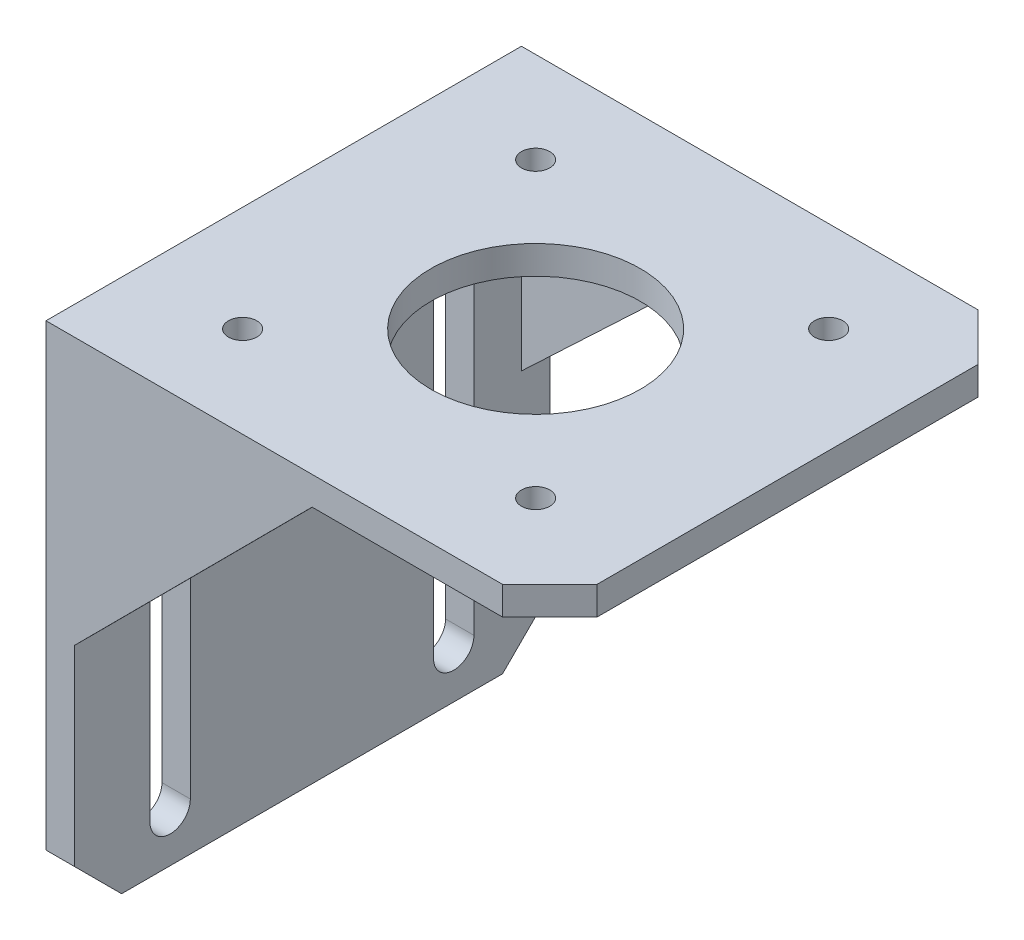
SolidWorks part; units mm, degrees
ref_plane "Front Plane" through (0, 0, 0) normal (0, 0, 1) x (1, 0, 0)
ref_plane "Top Plane" through (0, 0, 0) normal (0, 1, 0) x (1, 0, 0)
ref_plane "Right Plane" through (0, 0, 0) normal (1, 0, 0) x (0, 0, -1)
sketch "Sketch1" plane through (0, 0, 0) normal (1, 0, 0) x (0, 0, -1)
  line L1 (-14.9989, 23.6362) -> (35.3011, 23.6362)
  line L2 (-14.9989, 23.6362) -> (-14.9989, -29.8638)
  line L3 (-14.9989, -29.8638) -> (35.3011, -29.8638)
  line L4 (35.3011, 23.6362) -> (35.3011, -29.8638)
  line L5 (-6.9989, -24.8184) -> (-6.9989, 18.3152)
  line L6 (27.2711, 18.3152) -> (27.2711, -24.8184)
  line L7 (-2.7289, 18.3152) -> (-2.7289, -24.8184)
  line L10 (23.0011, 18.3152) -> (23.0011, -24.8184)
  arc A0 (-6.9989, 18.3152) -> (-2.7289, 18.3152) centre (-4.8639, 18.3152) cw
  arc A1 (-6.9989, -24.8184) -> (-2.7289, -24.8184) centre (-4.8639, -24.8184) ccw
  arc A2 (27.2711, 18.3152) -> (23.0011, 18.3152) centre (25.1361, 18.3152) ccw
  arc A3 (23.0011, -24.8184) -> (27.2711, -24.8184) centre (25.1361, -24.8184) ccw
  point P6 (-14.9989, -24.8184)
extrude "Boss-Extrude1" add sketch "Sketch1" along normal blind 3
sketch "Sketch3" plane through (3, 0, 0) normal (1, 0, 0) x (0, 0, -1)
  line L0 (35.3011, -29.8638) -> (35.3011, 23.6362) construction
  line L1 (-14.9989, 23.6362) -> (35.3011, 23.6362)
  line L2 (-14.9989, 23.6362) -> (-14.9989, 20.6362)
  line L3 (-14.9989, 20.6362) -> (35.3011, 20.6362)
  line L4 (35.3011, 23.6362) -> (35.3011, 20.6362)
extrude "Boss-Extrude3" add sketch "Sketch3" along normal blind 50.3
sketch "Sketch7" plane through (0, 0, -35.3011) normal (0, 0, -1) x (-1, 0, 0)
  line L0 (-3, 20.6362) -> (-28.15, 20.6362)
  line L1 (-53.3, 20.6362) -> (-3, 20.6362) construction
  line L2 (-28.15, 20.6362) -> (-3, -3.1138)
  line L3 (-3, -29.8638) -> (-3, 20.6362) construction
  line L10 (0, -29.8638) -> (0, 23.6362)
  line L11 (0, 23.6362) -> (-53.3, 23.6362)
  line L12 (-53.3, 23.6362) -> (-53.3, 20.6362)
  line L13 (-53.3, 20.6362) -> (-3, 20.6362)
  line L14 (-3, 20.6362) -> (-3, -29.8638)
  line L15 (-3, -29.8638) -> (0, -29.8638)
  line L20 (-3, 20.6362) -> (-3, -3.1138)
  point P2 (-3, -3.1138)
  point P10 (0, 0)
  point P14 (-28.15, 20.6362)
  dimension "D1" = 0
sketch "Sketch11" plane through (0, 0, 14.9989) normal (0, 0, 1) x (1, 0, 0)
  line L0 (3, 20.6362) -> (3, -4.6138)
  line L1 (3, 20.6362) -> (3, -29.8638) construction
  line L2 (3, -4.6138) -> (28.15, 20.6362)
  line L3 (53.3, 20.6362) -> (3, 20.6362) construction
  line L4 (28.15, 20.6362) -> (3, 20.6362)
  point P8 (3.6763, 20.6362)
  point P9 (3, -4.6138)
extrude "Boss-Extrude6" add sketch "Sketch11" against normal blind 3
extrude "Boss-Extrude7" add sketch "Sketch7" against normal blind 3 contours L2 L20 L0
sketch "Sketch12" plane through (0, 23.6362, 0) normal (0, 1, 0) x (1, 0, 0)
  circle A0 centre (42.15, 25.6511) radius 1.5
  circle A1 centre (42.15, -5.3489) radius 1.5
  circle A2 centre (11.15, 25.6511) radius 1.5
  circle A3 centre (11.15, -5.3489) radius 1.5
  circle A4 centre (26.65, 10.1511) radius 11.075
  point P4 (26.65, 10.1511)
extrude "Cut-Extrude1" cut sketch "Sketch12" against normal blind 3
chamfer "Chamfer2" distance 5 angle 45 1 edges at (53.3, 22.1362, -35.3011)
chamfer "Chamfer3" distance 5 angle 45 1 edges at (53.3, 22.1362, 14.9989)
chamfer "Chamfer4" distance 5 angle 45 1 edges at (1.5, -29.8638, 14.9989)
chamfer "Chamfer5" distance 5 angle 45 1 edges at (1.5, -29.8638, -35.3011)
